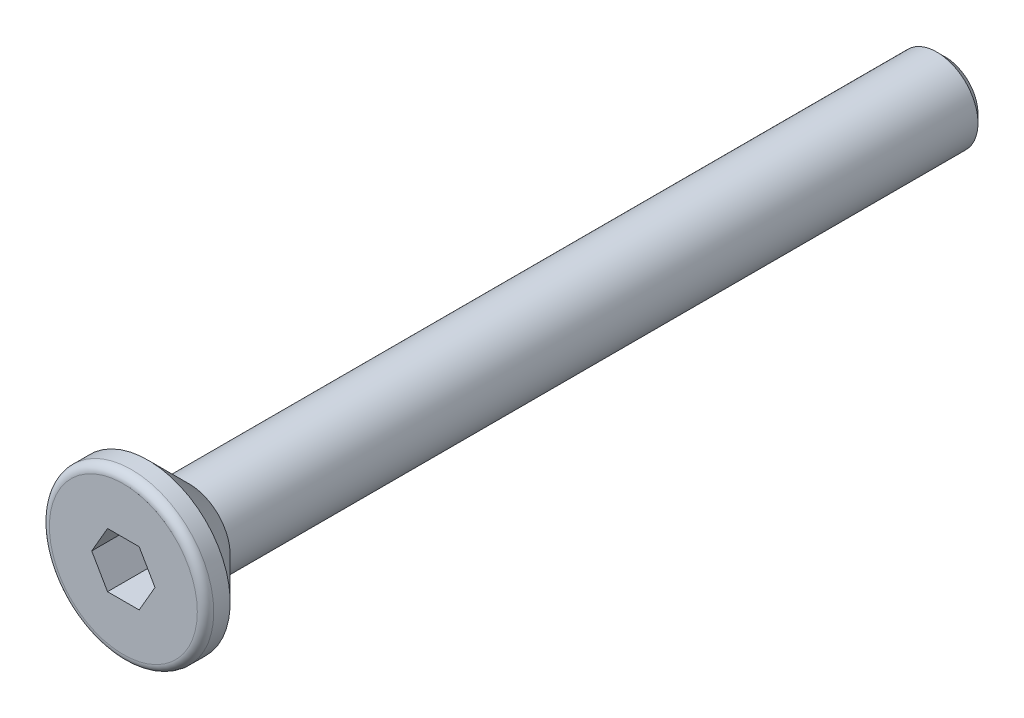
SolidWorks part; units mm, degrees
ref_plane "前视基准面" through (0, 0, 0) normal (0, 0, 1) x (1, 0, 0)
ref_plane "上视基准面" through (0, 0, 0) normal (0, 1, 0) x (1, 0, 0)
ref_plane "右视基准面" through (0, 0, 0) normal (1, 0, 0) x (0, 0, -1)
sketch "草图1" plane through (0, 0, 0) normal (1, 0, 0) x (0, 0, -1)
  line L0 (-15, 0) -> (-15, 3)
  line L1 (-15, 3) -> (-14.1, 3)
  line L2 (-14.1, 3) -> (-12.6, 1.5)
  line L3 (-12.6, 1.5) -> (14.7, 1.5)
  line L4 (14.7, 1.5) -> (15, 1.2)
  line L5 (15, 1.2) -> (15, 0)
  line L6 (15, 0) -> (-15, 0)
  dimension "D1" = 30
  dimension "D2" = 3
  dimension "D3" = 45
  dimension "D4" = 0.3
  dimension "D5" = 2.4
  dimension "D6" = 1.5
revolve "旋转1" add sketch "草图1" angle 360 about L6
sketch "草图2" plane through (0, 0, 15) normal (0, 0, 1) x (1, 0, 0)
  line L1 (1.1547, 0) -> (0.5774, 1)
  line L2 (0.5774, 1) -> (-0.5774, 1)
  line L3 (-0.5774, 1) -> (-1.1547, 0)
  line L4 (-1.1547, 0) -> (-0.5774, -1)
  line L5 (-0.5774, -1) -> (0.5774, -1)
  line L6 (0.5774, -1) -> (1.1547, 0)
  circle A0 centre (0, 0) radius 1 construction
  dimension "D1" = 2
extrude "切除-拉伸1" cut sketch "草图2" against normal blind 1.5
fillet "圆角1" radius 0.3 1 edges at (-3, 0, 15)
